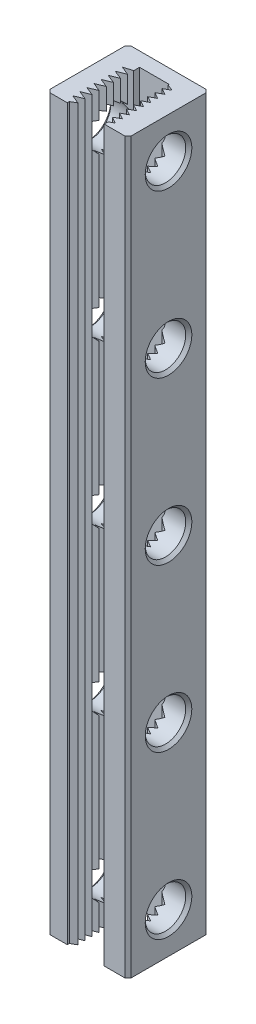
SolidWorks part; units mm, degrees
ref_plane "Front Plane" through (0, 0, 0) normal (0, 0, 1) x (1, 0, 0)
ref_plane "Top Plane" through (0, 0, 0) normal (0, 1, 0) x (1, 0, 0)
ref_plane "Right Plane" through (0, 0, 0) normal (1, 0, 0) x (0, 0, -1)
sketch "Sketch1" plane through (0, 0, 0) normal (0, 1, 0) x (1, 0, 0)
  line L1 (0, 0) -> (8, 0)
  line L2 (0, 0) -> (0, 8)
  line L3 (0, 8) -> (8, 8)
  line L4 (8, 0) -> (8, 8)
  dimension "D1" = 8
  dimension "D2" = 8
extrude "Boss-Extrude1" add sketch "Sketch1" along normal blind 300
sketch "Sketch2" plane through (0, 0, 0) normal (0, -1, 0) x (1, 0, 0)
  line L0 (5.652, 0) -> (2.0084, 0)
  line L1 (2.0084, 0) -> (2.0084, -0.2082)
  line L2 (2.0084, -0.2082) -> (2.54, -0.5151)
  line L3 (2.54, -0.5151) -> (1.6737, -0.8651)
  line L4 (1.6737, -0.8651) -> (2.54, -1.2151)
  line L5 (2.54, -1.2151) -> (1.6737, -1.5727)
  line L6 (1.6737, -1.5727) -> (2.54, -1.9151)
  line L7 (2.54, -1.9151) -> (1.6737, -2.2651)
  line L8 (1.6737, -2.2651) -> (2.54, -2.6151)
  line L9 (2.54, -2.6151) -> (1.6737, -2.9651)
  line L10 (1.6737, -2.9651) -> (2.54, -3.3151)
  line L11 (2.54, -3.3151) -> (1.6737, -3.6651)
  line L12 (1.6737, -3.6651) -> (2.54, -4.0151)
  line L13 (2.54, -4.0151) -> (1.6737, -4.3651)
  line L14 (1.6737, -4.3651) -> (2.54, -4.7151)
  line L15 (2.54, -4.7151) -> (1.6737, -5.0651)
  line L16 (1.6737, -5.0651) -> (2.54, -5.4151)
  line L17 (2.54, -5.4151) -> (1.6737, -5.7651)
  line L18 (1.6737, -5.7651) -> (2.54, -6.0264)
  line L19 (2.54, -6.0264) -> (2.54, -6.6)
  line L20 (2.54, -6.6) -> (5.46, -6.6)
  line L21 (5.46, -6.6) -> (5.46, -6.4988)
  line L22 (5.46, -6.4988) -> (6.1067, -6.2375)
  line L23 (6.1067, -6.2375) -> (5.46, -5.8875)
  line L24 (5.46, -5.8875) -> (6.1067, -5.5375)
  line L25 (6.1067, -5.5375) -> (5.46, -5.1875)
  line L26 (5.46, -5.1875) -> (6.1067, -4.8375)
  line L27 (6.1067, -4.8375) -> (5.46, -4.4875)
  line L28 (5.46, -4.4875) -> (6.1067, -4.1375)
  line L29 (6.1067, -4.1375) -> (5.46, -3.7875)
  line L30 (5.46, -3.7875) -> (6.1067, -3.4375)
  line L31 (6.1067, -3.4375) -> (5.46, -3.0875)
  line L32 (5.46, -3.0875) -> (6.1067, -2.7375)
  line L33 (6.1067, -2.7375) -> (5.46, -2.3875)
  line L34 (5.46, -2.3875) -> (6.1067, -2.0375)
  line L35 (6.1067, -2.0375) -> (5.46, -1.6875)
  line L36 (5.46, -1.6875) -> (6.1067, -1.3451)
  line L37 (6.1067, -1.3451) -> (5.46, -0.9875)
  line L38 (5.46, -0.9875) -> (6.1067, -0.6375)
  line L39 (6.1067, -0.6375) -> (5.652, -0.375)
  line L40 (5.652, -0.375) -> (5.652, 0)
  line L41 (0, -8) -> (0, 0) construction
  line L42 (8, -8) -> (0, -8) construction
  line L43 (0, 0) -> (8, 0) construction
  point P41 (0, 0)
  point P42 (0, 0)
  point P43 (0, 0)
  point P44 (0, 0)
  point P51 (0, 0)
  point P52 (0, 0)
  point P53 (4, -6.6)
  dimension "D1" = 2.92
  dimension "D2" = 0.8663
  dimension "D3" = 6.6
  dimension "D4" = 0.6467
  dimension "D5" = 4.433
  dimension "D6" = 4
extrude "Cut-Extrude1" cut sketch "Sketch2" against normal through all contours L0 L1 L2 L3 L4 L5 L6 L7 L8 L9 L10 L11 L12 L13 L14 L15 L16 L17 L18 L19 L20 L21 L22 L23 L24 L25 L26 L27 L28 L29 L30 L31 L32 L33 L34 L35 L36 L37 L38 L39 L40
sketch "Sketch3" plane through (8, 0, 0) normal (1, 0, 0) x (0, 0, -1)
  line L0 (0, 0) -> (8, 0) construction
  line L1 (8, 300) -> (8, 0) construction
  circle A0 centre (4, 4) radius 2
  dimension "D1" = 4
  dimension "D2" = 4
  dimension "D3" = 4
extrude "Cut-Extrude2" cut sketch "Sketch3" against normal through all
chamfer "Chamfer1" distance 0.3 angle 45 2 edges at (0, 4, -6) (8, 4, -6)
chamfer "Chamfer2" distance 0.3 angle 45 4 edges at (0, 150, -8) (0, 150, 0) (8, 150, -8) (8, 150, 0)
pattern_linear "LPattern1" count 19 spacing 16 along (0, 1, 0) of "Cut-Extrude2", "Chamfer1"
sketch "Sketch4" plane through (8, 0, 0) normal (1, 0, 0) x (0, 0, -1)
  line L0 (0.3, 300) -> (7.7, 300) construction
  line L1 (8, 300) -> (0, 300)
  line L2 (8, 300) -> (8, 72)
  line L3 (8, 72) -> (0, 72)
  line L4 (0, 300) -> (0, 72)
  line L5 (0, 0) -> (0, 300) construction
  line L6 (8, 300) -> (8, 0) construction
  line L7 (0.3, 0) -> (7.7, 0) construction
  point P7 (0, 0)
  dimension "D1" = 72
extrude "Cut-Extrude3" cut sketch "Sketch4" against normal through all
